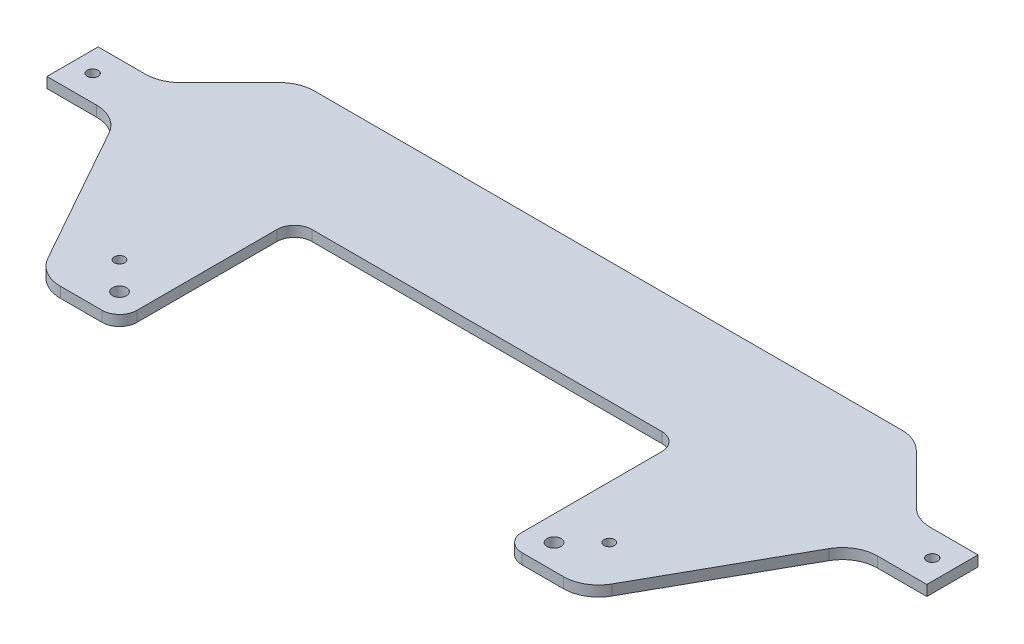
SolidWorks part; units mm, degrees
ref_plane "Alzado" through (0, 0, 0) normal (0, 0, 1) x (1, 0, 0)
ref_plane "Planta" through (0, 0, 0) normal (0, 1, 0) x (1, 0, 0)
ref_plane "Vista lateral" through (0, 0, 0) normal (1, 0, 0) x (0, 0, -1)
sketch "Croquis1" plane through (0, 0, 0) normal (0, 1, 0) x (1, 0, 0)
  line L0 (-27.8825, 0) -> (38.5584, 0) construction
  line L1 (-88.1, 42.3182) -> (88.1, 42.3182)
  line L2 (-77.75, -42.3182) -> (77.75, -42.3182)
  line L3 (-88.1, 42.3182) -> (-108.1, 22.3182)
  line L4 (-108.1, 22.3182) -> (-127.75, 22.3182)
  line L5 (0, 0) -> (0, 27.7067) construction
  line L6 (-127.75, 22.3182) -> (-127.75, 7.6818)
  line L7 (-127.75, 7.6818) -> (-105.75, 7.6818)
  line L8 (-105.75, 7.6818) -> (-77.75, -42.3182)
  line L9 (88.1, 42.3182) -> (108.1, 22.3182)
  line L10 (108.1, 22.3182) -> (127.75, 22.3182)
  line L11 (127.75, 22.3182) -> (127.75, 7.6818)
  line L12 (127.75, 7.6818) -> (105.75, 7.6818)
  line L13 (105.75, 7.6818) -> (77.75, -42.3182)
  dimension "D1" = 255.5
  dimension "D2" = 84.6363
  dimension "D3" = 19.65
  dimension "D4" = 22
  dimension "D5" = 22
  dimension "D6" = 50
  dimension "D7" = 50
  dimension "D8" = 50
  dimension "D9" = 20
  dimension "D10" = 20
extrude "Saliente-Extruir1" add sketch "Croquis1" along normal blind 3
fillet "Redondeo1" radius 10 8 edges at (88.1, 1.5, -42.3182) (-88.1, 1.5, -42.3182) (-77.75, 1.5, 42.3182) (77.75, 1.5, 42.3182) (108.1, 1.5, -22.3182) (105.75, 1.5, -7.6818) (-105.75, 1.5, -7.6818) (-108.1, 1.5, -22.3182)
sketch "Croquis2" plane through (0, 3, 0) normal (0, 1, 0) x (1, 0, 0)
  line L0 (0, 0) -> (0, -87.7887) construction
  line L1 (-119.9961, 22.3182) -> (-119.9961, 40.4374) construction
  line L2 (-112.2421, 22.3182) -> (-127.75, 22.3182) construction
  line L3 (-127.75, 15) -> (-123.2915, 15) construction
  line L4 (-127.75, 22.3182) -> (-127.75, 7.6818) construction
  line L5 (119.9961, 22.3182) -> (119.9961, 29.1715) construction
  line L6 (127.75, 22.3182) -> (112.2421, 22.3182) construction
  line L7 (115.6048, 15) -> (126.3231, 15) construction
  line L10 (-71.8888, -42.3182) -> (71.8888, -42.3182) construction
  circle A0 centre (70, -27.3182) radius 1.5
  circle A1 centre (-70, -27.3182) radius 1.5
  circle A2 centre (-119.9961, 15) radius 1.55
  circle A3 centre (119.9961, 15) radius 1.55
  circle A6 centre (-17.5, -17.3182) radius 1.5
  circle A7 centre (17.5, -17.3182) radius 1.5
  circle A8 centre (-17.5, -37.3182) radius 1.5
  circle A9 centre (17.5, -37.3182) radius 1.5
  dimension "D1" = 3.1
  dimension "D2" = 3.1
  dimension "D10" = 3
  dimension "D11" = 3
  dimension "D17" = 3
  dimension "D18" = 3
  dimension "D19" = 3
  dimension "D20" = 3
  dimension "D9" = 140
  dimension "D12" = 15
  dimension "D13" = 35
  dimension "D14" = 35
  dimension "D15" = 5
  dimension "D16" = 20
extrude "Cortar-Extruir1" cut sketch "Croquis2" against normal through all
sketch "Croquis4" plane through (0, 3, 0) normal (0, 1, 0) x (1, 0, 0)
  line L0 (-55, -42.3182) -> (-55, 7.6818)
  line L1 (-55, 7.6818) -> (55, 7.6818)
  line L2 (55, 7.6818) -> (55, -42.3182)
  line L3 (55, -42.3182) -> (-55, -42.3182)
  line L4 (0, 0) -> (0, 21.6247) construction
  line L5 (-71.8888, -42.3182) -> (71.8888, -42.3182) construction
  dimension "D1" = 110
  dimension "D2" = 50
extrude "Cortar-Extruir2" cut sketch "Croquis4" against normal through all
fillet "Redondeo2" radius 5 4 edges at (-55, 1.5, 42.3182) (55, 1.5, 42.3182) (55, 1.5, -7.6818) (-55, 1.5, -7.6818)
sketch "Croquis5" plane through (0, 3, 0) normal (0, 1, 0) x (1, 0, 0)
  line L0 (-127.75, 22.3182) -> (-127.75, 7.6818)
  line L1 (-127.75, 7.6818) -> (-123.75, 7.6818)
  line L2 (-127.75, 7.6818) -> (-111.6112, 7.6818) construction
  line L3 (-123.75, 7.6818) -> (-123.75, 22.3182)
  line L4 (-112.2421, 22.3182) -> (-127.75, 22.3182) construction
  line L5 (-123.75, 22.3182) -> (-127.75, 22.3182)
  line L6 (127.75, 22.3182) -> (127.75, 7.6818)
  line L7 (127.75, 7.6818) -> (123.75, 7.6818)
  line L8 (111.6112, 7.6818) -> (127.75, 7.6818) construction
  line L9 (123.75, 7.6818) -> (123.75, 22.3182)
  line L10 (127.75, 22.3182) -> (112.2421, 22.3182) construction
  line L11 (123.75, 22.3182) -> (127.75, 22.3182)
  dimension "D1" = 4
  dimension "D2" = 4
extrude "Cortar-Extruir3" cut sketch "Croquis5" against normal through all
sketch "Croquis6" plane through (123.75, 0, 0) normal (1, 0, 0) x (0, 0, -1)
  line L0 (7.6818, 3) -> (22.3182, 3)
  line L1 (22.3182, 3) -> (22.3182, 0)
  line L2 (22.3182, 0) -> (7.6818, 0)
  line L3 (22.3182, 0) -> (7.6818, 0) construction
  line L4 (7.6818, 0) -> (7.6818, 3) construction
  line L5 (7.6818, 3) -> (7.6818, 0)
extrude "Saliente-Extruir2" add sketch "Croquis6" along normal blind 2
sketch "Croquis8" plane through (-123.75, 0, 0) normal (-1, 0, 0) x (0, 0, 1)
  line L4 (-7.6818, 3) -> (-22.3182, 3)
  line L5 (-22.3182, 3) -> (-22.3182, 0)
  line L6 (-22.3182, 0) -> (-7.6818, 0)
  line L7 (-7.6818, 0) -> (-7.6818, 3)
  line L8 (-7.6818, 3) -> (-22.3182, 3)
  line L9 (-22.3182, 3) -> (-22.3182, 0)
  line L10 (-22.3182, 0) -> (-7.6818, 0)
  line L11 (-7.6818, 0) -> (-7.6818, 3)
  dimension "D1" = 0
extrude "Saliente-Extruir3" add sketch "Croquis8" along normal blind 2
sketch "Croquis9" plane through (0, 3, 0) normal (0, 1, 0) x (1, 0, 0)
  circle A0 centre (-62.1, -35.2182) radius 2
  dimension "D1" = 4
extrude "Cortar-Extruir4" cut sketch "Croquis9" against normal through all
mirror "Simetría1" about plane through (0, 0, 0) normal (1, 0, 0) of "Cortar-Extruir4"
